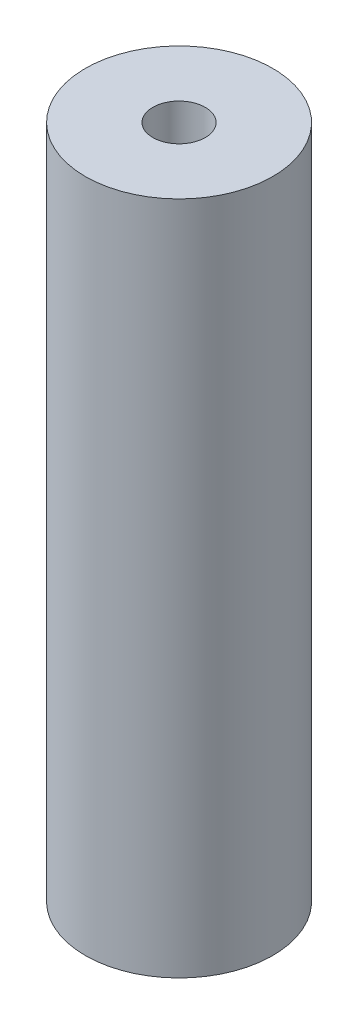
SolidWorks part; units mm, degrees
ref_plane "Front" through (0, 0, 0) normal (0, 0, 1) x (1, 0, 0)
ref_plane "Top" through (0, 0, 0) normal (0, 1, 0) x (1, 0, 0)
ref_plane "Right" through (0, 0, 0) normal (1, 0, 0) x (0, 0, -1)
sketch "Sketch1" plane through (0, 0, 0) normal (0, 1, 0) x (1, 0, 0)
  circle A0 centre (0, 0) radius 7.5
  dimension "D1" = 15
extrude "Boss-Extrude1" add sketch "Sketch1" along normal blind 54
hole_wizard "M5 Tapped Hole1" positions "Sketch2" profile "Sketch3" tap size "M5" standard "ISO"
sketch "Sketch2" plane through (0, 54, 0) normal (0, 1, 0) x (1, 0, 0)
  point P0 (0, 0)
sketch "Sketch3" plane through (0, 54, 0) normal (1, 0, 0) x (0, 0, 1)
  line L0 (0, 0) -> (0, 13.6618)
  line L1 (0, 13.6618) -> (2.1, 12.4)
  line L2 (2.1, 12.4) -> (2.1, 0)
  line L5 (2.1, 0) -> (0, 0)
  line L10 (0, 13.6618) -> (-2.1, 12.4) construction
  line L11 (0, -6.35) -> (0, 107.95) construction
  dimension "Tap Drill Dia." = 4.2
  dimension "Tap Drill Depth" = 12.4
  dimension "Drill Angle" = 118
cosmetic thread "Hole Thread1" parameters "D1"=10, "D2"=5
ref_plane "Plane1" through (0, 27, 0) normal (0, 1, 0) x (1, 0, 0)
mirror "Mirror1" about plane through (0, 27, 0) normal (0, 1, 0) of "M5 Tapped Hole1"
cosmetic thread "Hole Thread2" parameters "D1"=10, "D2"=5
